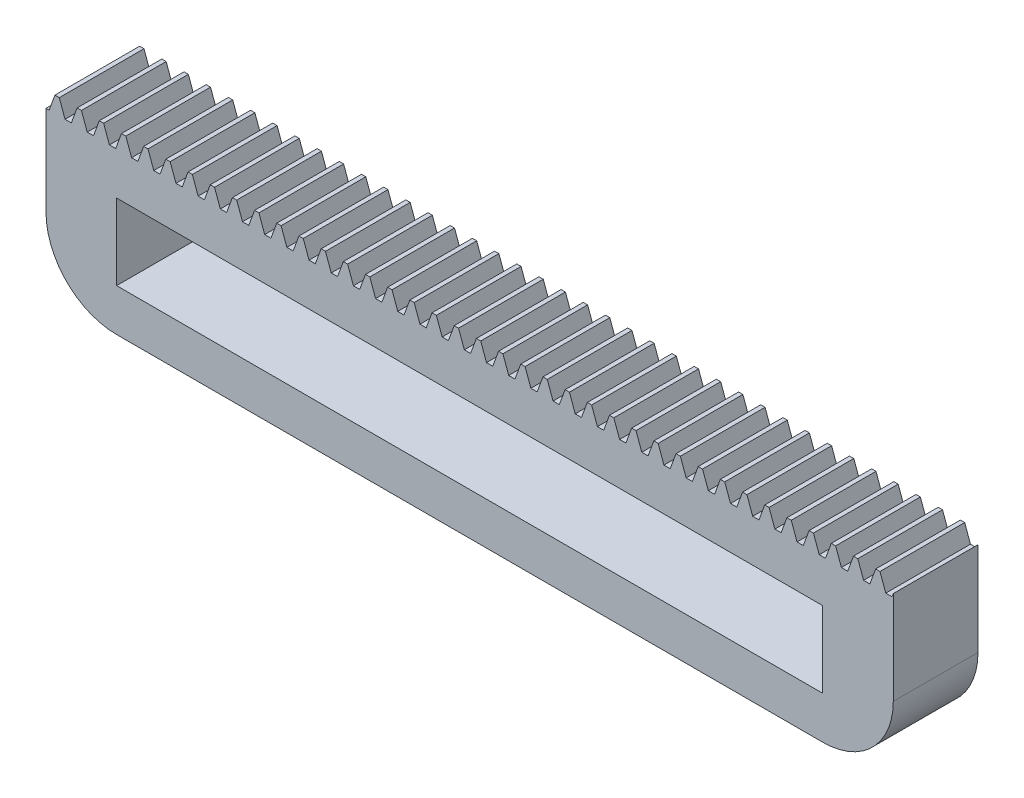
SolidWorks part; units mm, degrees
extrude "Blank" add sketch "BlankSke" against normal blind 6
sketch "BlankSke" plane through (0, 0, 0) normal (0, 0, 1) x (1, 0, 0)
  line L1 (0, 0) -> (60, 0)
  line L2 (0, 0) -> (0, 12.5)
  line L3 (0, 12.5) -> (60, 12.5)
  line L4 (60, 0) -> (60, 12.5)
  dimension "Length" = 60
  dimension "Blank_height" = 12.5
ref_plane "Plane1" through (0, 0, 0) normal (0, 0, 1) x (1, 0, 0)
ref_plane "Plane2" through (0, 0, 0) normal (0, 1, 0) x (1, 0, 0)
ref_plane "Plane3" through (0, 0, 0) normal (1, 0, 0) x (0, 0, -1)
sketch "HoldingSke" plane through (0, 0, 0) normal (0, 1, 0) x (1, 0, 0)
  line L0 (0, 0) -> (0.2783, 1.9805)
  line L1 (-15, 0) -> (100, 0) construction
  line L2 (0, 0) -> (-2.1039, 2.3779)
  line L3 (0, 0) -> (-11.863, 4.5341)
  line L4 (0, 0) -> (-5.4348, 6.7114)
  line L5 (0, 0) -> (-23.7986, -8.8762)
  line L6 (0, 0) -> (-10.5278, -7.1032)
  line L9 (-71.009, 38.7566) -> (116.9296, 107.1606)
  line L10 (-76.2, 2.8779) -> (-64.2, 2.8779)
  line L11 (0, 0) -> (-6, 0)
  line L12 (-76.2, 101.6) -> (-76.181, 101.6)
  line L13 (24.9733, 27.94) -> (52.9518, 28.4284)
  line L14 (24.9733, 27.94) -> (24.9743, 27.94)
  line L15 (24.9733, 27.94) -> (100.4006, 29.5858)
  circle A0 centre (0, 0) radius 19.05
  circle A1 centre (0, 0) radius 6
  circle A2 centre (0, 0) radius 12.7
  dimension "MPH" = 12
  dimension "Diameter" = 38.1
  dimension "Num_teeth" = 129
  dimension "Pitch" = 2
  dimension "Show_teeth" = 998
  dimension "Thickness" = 12.7
  dimension "Ap" = 20
  dimension "Pitch_height" = 12
  dimension "Width" = 6
  dimension "Backlash" = 0.019
  dimension "Addendum_fac" = 1
  dimension "Dedendum_fac" = 1.25
  dimension "Clearance_fac" = 0.25
  dimension "Dedendum_add" = 0.001
  dimension "Length" = 200
  dimension "Module" = 0.5
sketch "TooCutSkeIll" plane through (0, 0, 0) normal (0, 0, 1) x (1, 0, 0)
  line L0 (-0.6269, 12.4868) -> (-0.2524, 11.4579)
  line L1 (-0.134, 11.375) -> (0.134, 11.375)
  line L2 (0.2524, 11.4579) -> (0.6269, 12.4868)
  line L3 (60, 12.5) -> (0, 12.5) construction
  line L4 (0, 0) -> (0, 64.897) construction
  line L5 (-13.208, 12) -> (12.954, 12) construction
  line L6 (0, 0) -> (60, 0) construction
  line L7 (0.4497, 12) -> (0.4497, 48.7463) construction
  line L8 (-0.4497, 12) -> (-0.4497, 48.7463) construction
  line L9 (0.6457, 12.5) -> (0.6457, 12.5254)
  line L10 (-0.6457, 12.5) -> (-0.6457, 12.5254)
  line L11 (-0.6457, 12.5254) -> (0.6457, 12.5254)
  arc A0 (0.134, 11.375) -> (0.2524, 11.4579) centre (0.134, 11.501) ccw
  arc A1 (-0.2524, 11.4579) -> (-0.134, 11.375) centre (-0.134, 11.501) ccw
  arc A2 (0.6457, 12.5) -> (0.6269, 12.4868) centre (0.6457, 12.48) ccw
  arc A3 (-0.6269, 12.4868) -> (-0.6457, 12.5) centre (-0.6457, 12.48) ccw
  dimension "Pitch_height" = 12
  dimension "Addendum_plus" = 0.5254
  dimension "Pressure_angle" = 20
  dimension "Gap_width" = 0.8994
  dimension "Dedendum" = 0.625
extrude "ToothCutIll" [suppressed] cut sketch "TooCutSkeIll" against normal through all
sketch "TooCutSkeSim" plane through (0, 0, 0) normal (0, 0, 1) x (1, 0, 0)
  line L0 (0.2222, 11.375) -> (-0.2222, 11.375)
  line L1 (0.6409, 12.5254) -> (0.2222, 11.375)
  line L2 (0, 17.4625) -> (0, 53.467) construction
  line L3 (0.6409, 12.5254) -> (-0.6409, 12.5254)
  line L6 (-0.6409, 12.5254) -> (-0.2222, 11.375)
  line L9 (-0.4497, 12) -> (0.4497, 12) construction
  line L10 (0, 0) -> (60, 0) construction
  line L11 (0.4497, 12) -> (0.4497, 53.467) construction
  line L12 (-0.4497, 12) -> (-0.4497, 53.467) construction
  dimension "Pitch_height" = 12
  dimension "Addendum_plus" = 0.5254
  dimension "Pressure_angle" = 20
  dimension "Gap_width" = 0.8994
  dimension "Dedendum" = 0.625
extrude "ToothCutSim" cut sketch "TooCutSkeSim" against normal through all
pattern_linear "TeethCuts" count 39 spacing 1.5708 along (1, 0, 0) of "ToothCutIll", "ToothCutSim"
sketch "Sketch1" plane through (0, 0, 0) normal (0, -1, 0) x (1, 0, 0)
  line L1 (0, 0) -> (60, 0)
  line L2 (0, 0) -> (0, -6)
  line L3 (0, -6) -> (60, -6)
  line L4 (60, 0) -> (60, -6)
extrude "Boss-Extrude1" add sketch "Sketch1" along normal blind 10
ref_plane "Plane5" through (0, -10, 0) normal (0, -1, 0) x (-1, 0, 0)
mirror "Mirror1" [suppressed] about plane through (0, -10, 0) normal (0, -1, 0)
fillet "Fillet2" [suppressed] radius 20
sketch "Sketch4" plane through (0, 0, 0) normal (0, 0, 1) x (1, 0, 0)
  line L1 (-2.9931, 0) -> (85.891, 0)
  line L2 (-2.9931, 0) -> (-2.9931, -15.472)
  line L3 (-2.9931, -15.472) -> (85.891, -15.472)
  line L4 (85.891, 0) -> (85.891, -15.472)
extrude "Cut-Extrude3" cut sketch "Sketch4" against normal through all
sketch "Sketch3" plane through (0, 0, 0) normal (0, 0, 1) x (1, 0, 0)
  line L0 (0, 5.6875) -> (60, 5.6875) construction
  line L1 (60, 0) -> (0, 0) construction
  line L2 (0, 11.375) -> (0, 0) construction
  line L9 (5, 3) -> (55, 3)
  line L10 (5, 3) -> (5, 8.375)
  line L11 (5, 8.375) -> (55, 8.375)
  line L12 (55, 3) -> (55, 8.375)
  line L13 (5, 3) -> (55, 8.375) construction
  line L14 (5, 8.375) -> (55, 3) construction
  point P5 (40, 0)
  point P8 (30, 5.6875)
  dimension "D1" = 5
  dimension "D2" = 3
  dimension "D3" = 30
extrude "Cut-Extrude2" cut sketch "Sketch3" against normal blind 10
fillet "Fillet3" radius 5 2 edges at (60, 0, -3) (0, 0, -3)
equation "' \"Module@HoldingSke\" = 6.35"
equation "' \"Num_teeth@HoldingSke\" = 12"
equation "' \"Ap@HoldingSke\" =  20"
equation "' \"Ap@HoldingSke\" = 20"
equation "' \"Width@HoldingSke\" = 0.25 * 25.4"
equation "' \"Show_teeth@HoldingSke\" = 500"
equation "' \"Backlash@HoldingSke\" = 0.009 * 25.4"
equation "' \"Addendum_fac@HoldingSke\" = 1.0"
equation "' \"Dedendum_fac@HoldingSke\" = 1.25"
equation "' \"Dedendum_add@HoldingSke\" = 0.00005 * 25.4"
equation "' \"Clearance_fac@HoldingSke\" = 0.25"
equation "' \"Pitch_height@HoldingSke\" = 1 * 25.4"
equation "' \"Length@HoldingSke\" = 4.71 * 25.4"
equation "\"Pitch@HoldingSke\" = 1 / \"Module@HoldingSke\""
equation "\"MPH@HoldingSke\" = \"Dedendum_fac@HoldingSke\" / \"Pitch@HoldingSke\" + 2 * \"Dedendum_add@HoldingSke\" + 0.002 * 25.4"
equation "\"MPH@HoldingSke\" = ((sgn( \"MPH@HoldingSke\" - \"Pitch_height@HoldingSke\")+1)*( \"MPH@HoldingSke\" - \"Pitch_height@HoldingSke\"))/2 + \"Pitch_height@HoldingSke\""
equation "\"Blank_height@BlankSke\" = \"Pitch_height@HoldingSke\" + \"Addendum_fac@HoldingSke\"  / \"Pitch@HoldingSke\" "
equation "\"Face_width@Blank\" = \"Width@HoldingSke\""
equation "\"Pressure_angle@TooCutSkeIll\" = \"Ap@HoldingSke\""
equation "\"Addendum_plus@TooCutSkeIll\" =  \"Addendum_fac@HoldingSke\"  / \"Pitch@HoldingSke\" + 0.001 *25.4"
equation "\"Dedendum@TooCutSkeIll\" = \"Dedendum_fac@HoldingSke\"  / \"Pitch@HoldingSke\""
equation "\"Pitch_height@TooCutSkeIll\" =  \"MPH@HoldingSke\""
equation "\"Gap_width@TooCutSkeIll\" = 3.14159265 / 2 / \"Pitch@HoldingSke\" + 6 * \"Backlash@HoldingSke\""
equation "\"Pressure_angle@TooCutSkeSim\" = \"Ap@HoldingSke\""
equation "\"Addendum_plus@TooCutSkeSim\" =  \"Addendum_fac@HoldingSke\"  / \"Pitch@HoldingSke\" + 0.001 * 25.4"
equation "\"Dedendum@TooCutSkeSim\" = \"Dedendum_fac@HoldingSke\"  / \"Pitch@HoldingSke\""
equation "\"Pitch_height@TooCutSkeSim\" =  \"MPH@HoldingSke\""
equation "\"Gap_width@TooCutSkeSim\" = 3.14159265 / 2 / \"Pitch@HoldingSke\" + 6 * \"Backlash@HoldingSke\""
equation "\"Root_fillet@TooCutSkeIll\" = \"Clearance_fac@HoldingSke\" / \"Pitch@HoldingSke\" + \"Dedendum_add@HoldingSke\""
equation "\"Break_rad@TooCutSkeIll\" = 0.02 / \"Pitch@HoldingSke\" * 2"
equation "\"Linear_pitch@TeethCuts\" = 3.14159265 / \"Pitch@HoldingSke\""
equation "\"Num_teeth@HoldingSke\" = int( ( \"Length@HoldingSke\" + 0 ) / (3.14159265 / \"Pitch@HoldingSke\")) + 0.9999  + 1"
equation " \"Num_teeth@TeethCuts\" = int( \"Show_teeth@HoldingSke\" ) + 1"
equation " \"Num_teeth@TeethCuts\" = ((sgn( \"Num_teeth@TeethCuts\" - \"Num_teeth@HoldingSke\" )-1)*( \"Num_teeth@TeethCuts\" - \"Num_teeth@HoldingSke\" ))/-2+ \"Num_teeth@HoldingSke\""
equation " \"Num_teeth@TeethCuts\" = ((sgn( \"Num_teeth@TeethCuts\" - 2.0)+1)*( \"Num_teeth@TeethCuts\" - 2.0))/2 +2.0"
